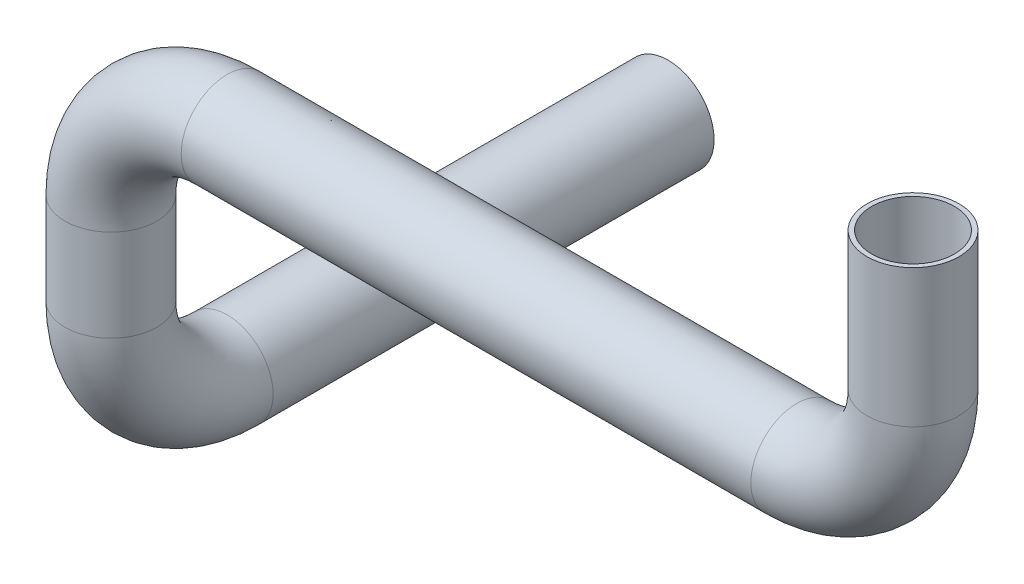
SolidWorks part; units mm, degrees
material "201 Annealed Stainless Steel (SS)"
ref_plane "Front Plane" through (0, 0, 0) normal (0, 0, 1) x (1, 0, 0)
ref_plane "Top Plane" through (0, 0, 0) normal (0, 1, 0) x (1, 0, 0)
ref_plane "Right Plane" through (0, 0, 0) normal (1, 0, 0) x (0, 0, -1)
sketch "Sketch1" plane through (0, 0, 0) normal (0, 1, 0) x (1, 0, 0)
  circle A0 centre (0, 0) radius 5
  dimension "D1" = 10
sketch "Sketch2" plane through (0, 0, 0) normal (0, 0, 1) x (1, 0, 0)
  line L0 (0, 0) -> (0, 10)
  line L1 (12.65, 22.65) -> (74.65, 22.65)
  line L2 (87.3, 35.3) -> (87.3, 50.3)
  arc A0 (74.65, 22.65) -> (87.3, 35.3) centre (74.65, 35.3) ccw
  arc A1 (0, 10) -> (12.65, 22.65) centre (12.65, 10) cw
  point P9 (0, 13.4311)
  point P10 (54.3891, 47.5766)
  point P11 (54.7657, 55.3639)
  dimension "D1" = 12.65
  dimension "D2" = 10
  dimension "D3" = 15
  dimension "D4" = 62
sweep "Sweep1" add profiles "Sketch1" path "Sketch2"
sketch "Sketch3" plane through (0, 0, 0) normal (0, -1, 0) x (1, 0, 0)
  circle A1 centre (0, 0) radius 5
  circle A2 centre (0, 0) radius 5
  dimension "D1" = 0
sketch "Sketch5" plane through (0, 0, 0) normal (1, 0, 0) x (0, 0, -1)
  line L0 (12.65, -12.65) -> (60.65, -12.65)
  arc A0 (0, 0) -> (12.65, -12.65) centre (12.65, 0) ccw
  point P3 (0, 0)
  point P8 (0, 0)
  dimension "D2" = 12.65
  dimension "D1" = 48
sweep "Sweep2" add profiles "Sketch3" path "Sketch5"
shell "Shell1" thickness 0.5
